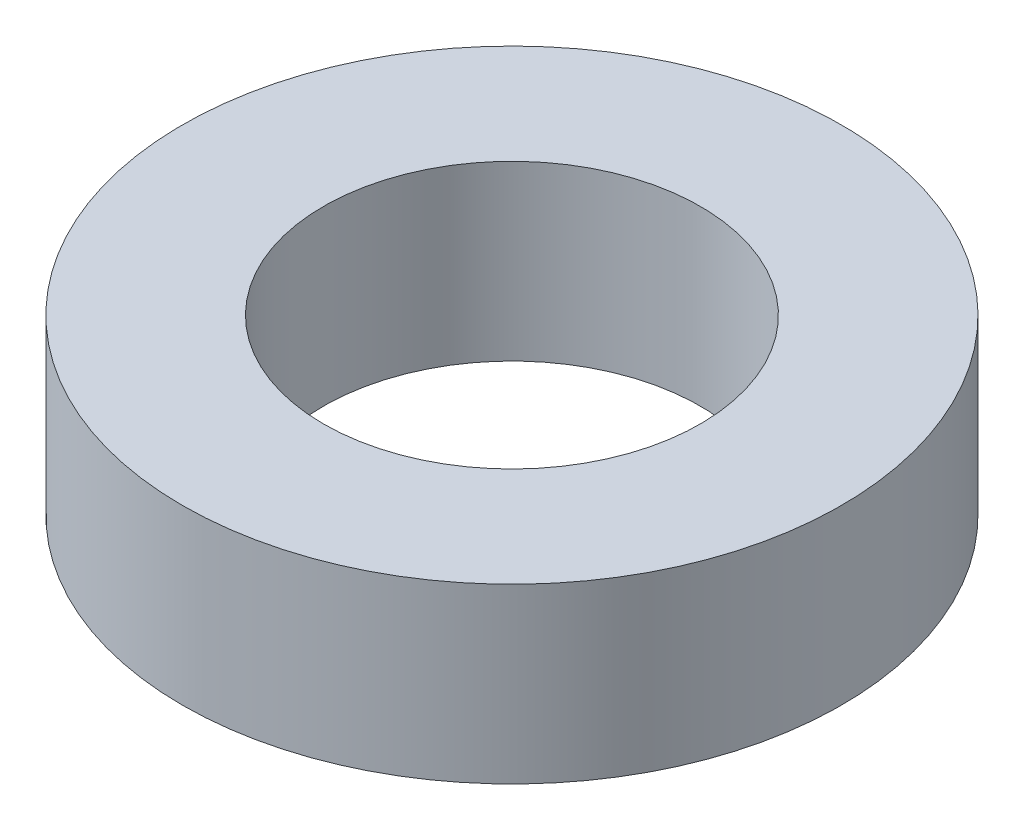
SolidWorks part; units mm, degrees
ref_plane "Front" through (0, 0, 0) normal (0, 0, 1) x (1, 0, 0)
ref_plane "Top" through (0, 0, 0) normal (0, 1, 0) x (1, 0, 0)
ref_plane "Right" through (0, 0, 0) normal (1, 0, 0) x (0, 0, -1)
sketch "Sketch1" plane through (0, 0, 0) normal (0, 1, 0) x (1, 0, 0)
  circle A0 centre (0, 0) radius 5.334
  circle A1 centre (0, 0) radius 3.05
  dimension "D1" = 10.668
  dimension "D2" = 6.1
extrude "Boss-Extrude1" add sketch "Sketch1" along normal blind 2.8
